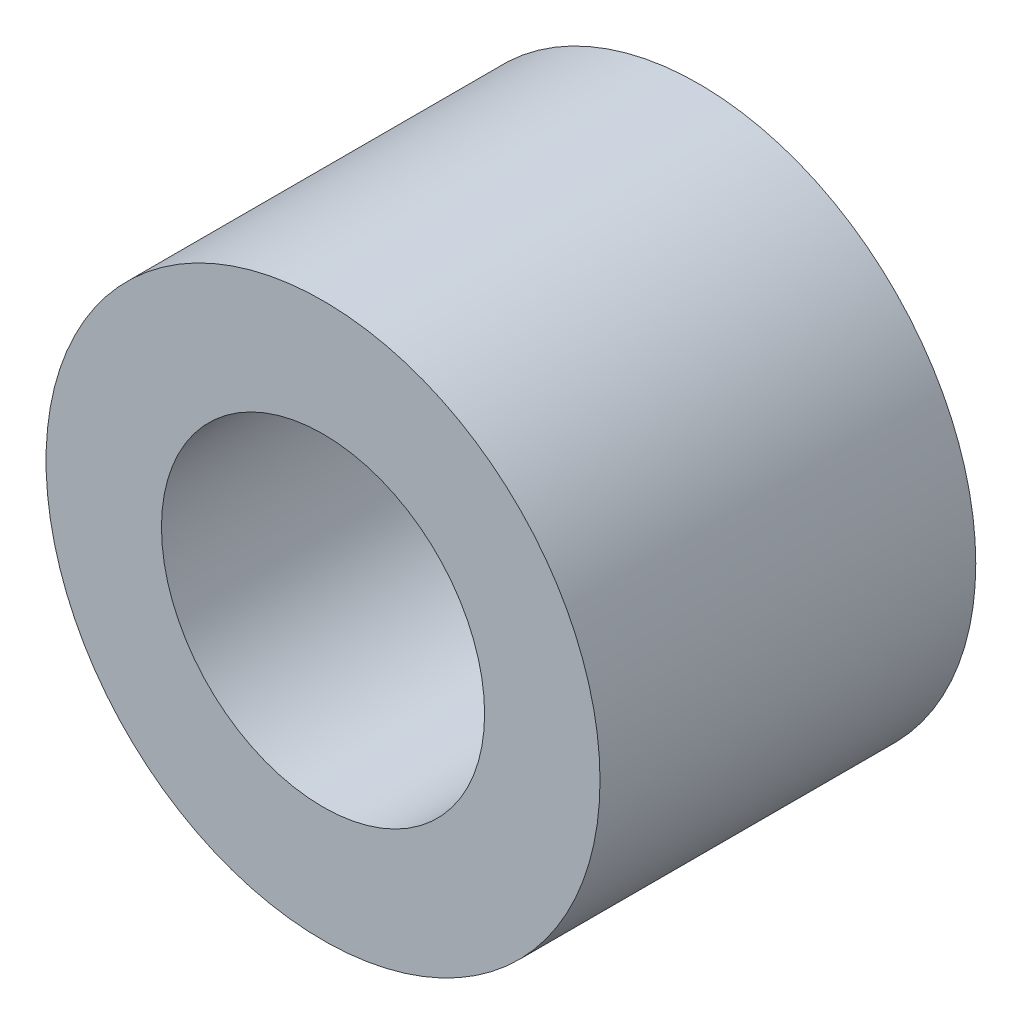
SolidWorks part; units mm, degrees
ref_plane "Front" through (0, 0, 0) normal (0, 0, 1) x (1, 0, 0)
ref_plane "Top" through (0, 0, 0) normal (0, 1, 0) x (1, 0, 0)
ref_plane "Right" through (0, 0, 0) normal (1, 0, 0) x (0, 0, -1)
sketch "Sketch1" plane through (0, 0, 0) normal (0, 0, 1) x (1, 0, 0)
  circle A0 centre (0, 0) radius 17.78
  circle A1 centre (0, 0) radius 30.48
  dimension "D1" = 35.56
  dimension "D2" = 60.96
extrude "Boss-Extrude1" add sketch "Sketch1" along normal blind 41.35
